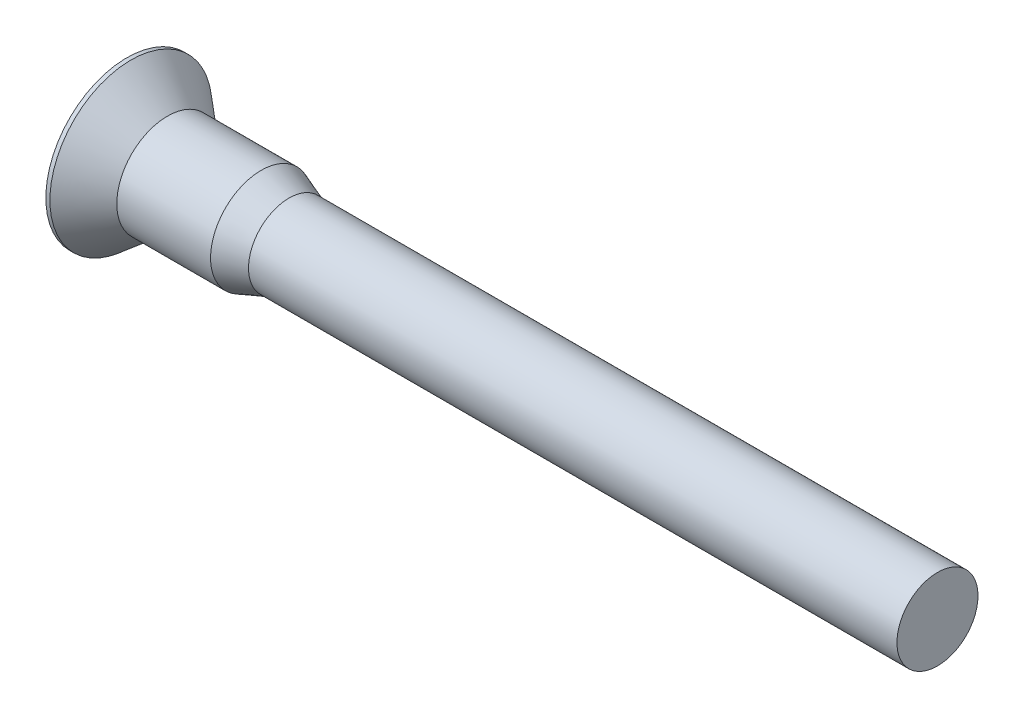
SolidWorks part; units mm, degrees
ref_plane "Front Plane" through (0, 0, 0) normal (0, 0, 1) x (1, 0, 0)
ref_plane "Top Plane" through (0, 0, 0) normal (0, 1, 0) x (1, 0, 0)
ref_plane "Right Plane" through (0, 0, 0) normal (1, 0, 0) x (0, 0, -1)
sketch "Sketch1" plane through (0, 0, 0) normal (0, 1, 0) x (1, 0, 0)
  line L0 (0, 0) -> (0, 4)
  line L2 (2, 2.5) -> (6.6277, 2.5)
  line L3 (6.6277, 2.5) -> (8, 2)
  line L4 (8, 2) -> (40, 2)
  line L5 (40, 2) -> (40, 0)
  line L6 (40, 0) -> (0, 0)
  line L7 (0, 4) -> (0.2, 4)
  line L8 (0.2, 4) -> (2, 2.5)
  dimension "D1" = 4
  dimension "D2" = 8
  dimension "D3" = 2.5
  dimension "D4" = 2
  dimension "D5" = 40
  dimension "D6" = 0.2
revolve "Revolve1" add sketch "Sketch1" angle 360 about L6
sketch "Sketch2" plane through (0, 0, 0) normal (-1, 0, 0) x (0, 0, 1)
  line L1 (1.9873, 1.1764) -> (-0.0252, 2.3093)
  line L2 (-0.0252, 2.3093) -> (-2.0125, 1.1328)
  line L3 (-2.0125, 1.1328) -> (-1.9873, -1.1764)
  line L4 (-1.9873, -1.1764) -> (0.0252, -2.3093)
  line L5 (0.0252, -2.3093) -> (2.0125, -1.1328)
  line L6 (2.0125, -1.1328) -> (1.9873, 1.1764)
  circle A0 centre (0, 0) radius 2 construction
  dimension "D1" = 4
extrude "Cut-Extrude1" cut sketch "Sketch2" against normal blind 2
